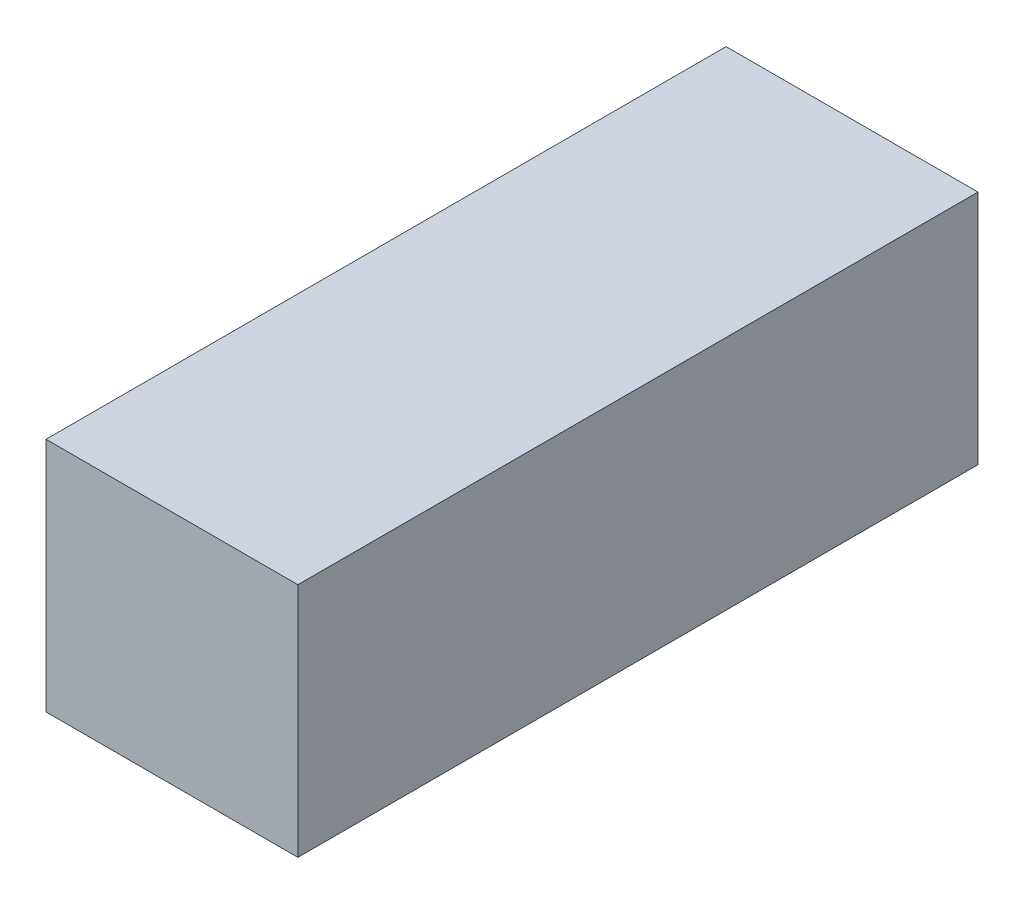
SolidWorks part; units mm, degrees
ref_plane "Front Plane" through (0, 0, 0) normal (0, 0, 1) x (1, 0, 0)
ref_plane "Top Plane" through (0, 0, 0) normal (0, 1, 0) x (1, 0, 0)
ref_plane "Right Plane" through (0, 0, 0) normal (1, 0, 0) x (0, 0, -1)
sketch "Sketch1" plane through (0, 0, 0) normal (0, 0, 1) x (1, 0, 0)
  line L1 (0, 0) -> (-26.6667, 0)
  line L2 (0, 0) -> (0, 25)
  line L3 (0, 25) -> (-26.6667, 25)
  line L4 (-26.6667, 0) -> (-26.6667, 25)
  dimension "D1" = 26.6667
  dimension "D2" = 25
extrude "Boss-Extrude1" add sketch "Sketch1" along normal blind 72
